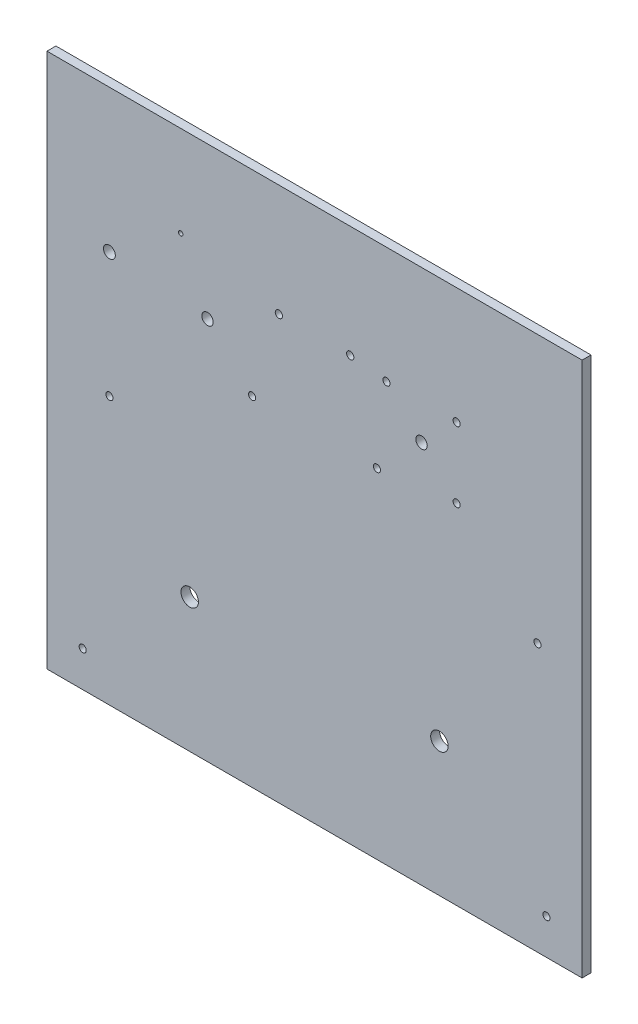
SolidWorks part; units mm, degrees
ref_plane "Front Plane" through (0, 0, 0) normal (0, 0, 1) x (1, 0, 0)
ref_plane "Top Plane" through (0, 0, 0) normal (0, 1, 0) x (1, 0, 0)
ref_plane "Right Plane" through (0, 0, 0) normal (1, 0, 0) x (0, 0, -1)
sketch "Sketch1" plane through (0, 0, 0) normal (0, 0, 1) x (1, 0, 0)
  line L0 (-25.4, 301.365) -> (25.4, 301.365) construction
  line L1 (0, 381) -> (0, 0) construction
  line L2 (-146.05, 190.5) -> (-146.05, -8.5714) construction
  line L3 (51.2, 298.05) -> (51.2, 248.05) construction
  line L4 (51.2, 248.05) -> (101.2, 248.05) construction
  line L5 (101.2, 248.05) -> (101.2, 298.05) construction
  line L6 (190.5, 381) -> (-190.5, 381)
  line L7 (101.2, 298.05) -> (51.2, 298.05) construction
  line L8 (51.2, 298.05) -> (101.2, 248.05) construction
  line L9 (101.2, 298.05) -> (51.2, 248.05) construction
  line L10 (-76.2, 273.05) -> (76.2, 273.05) construction
  line L11 (-44.45, 241.3) -> (44.45, 241.3) construction
  line L13 (190.5, 381) -> (190.5, 0)
  line L14 (-190.5, 381) -> (-190.5, 0)
  line L16 (-190.5, 0) -> (190.5, 0)
  circle A0 centre (76.2, 273.05) radius 4.064
  circle A1 centre (44.45, 241.3) radius 2.54
  circle A2 centre (88.9, 95.25) radius 6.223
  circle A3 centre (-165.1, 25.4) radius 2.54
  circle A4 centre (101.2, 298.05) radius 2.54
  circle A5 centre (158.75, 190.5) radius 2.54
  circle A6 centre (101.2, 248.05) radius 2.54
  circle A7 centre (165.1, 25.4) radius 2.54
  circle A8 centre (-88.9, 95.25) radius 6.223
  circle A10 centre (-146.05, 190.5) radius 2.54
  circle A11 centre (51.2, 298.05) radius 2.54
  circle A12 centre (-25.4, 301.365) radius 2.5797
  circle A13 centre (25.4, 301.365) radius 2.5797
  circle A14 centre (-44.45, 241.3) radius 2.54
  circle A15 centre (-76.2, 273.05) radius 4.064
  circle A17 centre (-95.25, 316.23) radius 1.5875
  point P4 (0, 301.365)
  point P6 (0, 241.3)
  point P18 (0, 273.05)
  dimension "D2" = 50.8
  dimension "D4" = 381
  dimension "D5" = 381
  dimension "D6" = 25.4
  dimension "D7" = 25.4
  dimension "D8" = 95.25
  dimension "D9" = 101.6
  dimension "D10" = 190.5
  dimension "D11" = 44.45
  dimension "D12" = 114.3
  dimension "D13" = 50
  dimension "D14" = 50
  dimension "D15" = 273.05
  dimension "D16" = 241.3
  dimension "D17" = 146.05
  dimension "D19" = 316.23
  dimension "D20" = 95.25
  dimension "D21" = 31.75
  dimension "D22" = 190.5
extrude "Boss-Extrude1" add sketch "Sketch1" along normal blind 6.35
hole_wizard "3/8-24 Tapped Hole2" positions "Sketch5" profile "Sketch4" tap size "3/8-24" standard "Ansi Inch" end condition through all
sketch "Sketch5" plane through (0, 0, 6.35) normal (0, 0, 1) x (1, 0, 0)
  line L0 (-146.05, 190.5) -> (-146.05, 279.4) construction
  point P0 (-146.05, 279.4)
  dimension "D1" = 88.9
sketch "Sketch4" plane through (-146.05, 279.4, 6.35) normal (1, 0, 0) x (0, -1, 0)
  line L0 (0, 0) -> (0, 6.35)
  line L1 (0, 6.35) -> (4.2164, 6.35)
  line L2 (4.2164, 6.35) -> (4.2164, 0)
  line L5 (4.2164, 0) -> (0, 0)
  line L11 (0, -6.35) -> (0, 107.95) construction
  dimension "Thru Tap Drill Dia." = 8.4328
  dimension "Thru Tap Drill Depth" = 6.35
cosmetic thread "Hole Thread1" parameters "D2"=9.525
